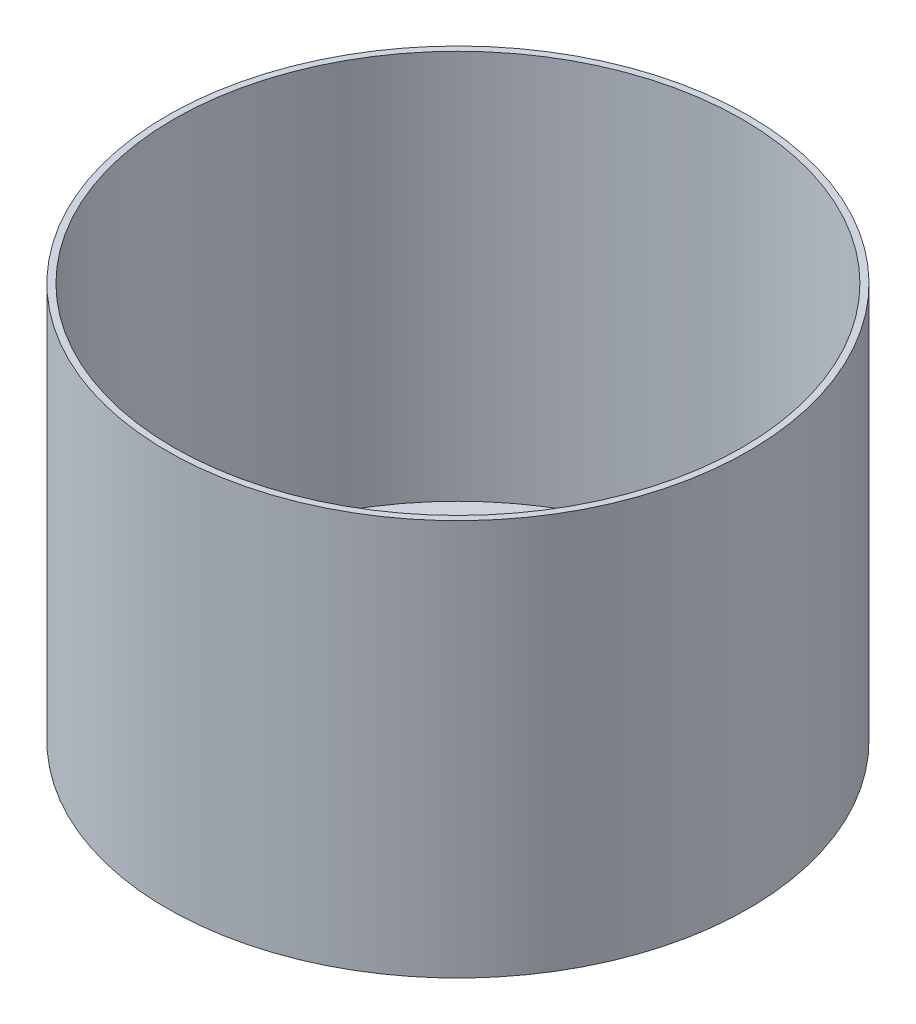
SolidWorks part; units mm, degrees
ref_plane "Front Plane" through (0, 0, 0) normal (0, 0, 1) x (1, 0, 0)
ref_plane "Top Plane" through (0, 0, 0) normal (0, 1, 0) x (1, 0, 0)
ref_plane "Right Plane" through (0, 0, 0) normal (1, 0, 0) x (0, 0, -1)
sketch "Compartment" plane through (0, 0, 0) normal (0, 0, 1) x (1, 0, 0)
  line L3 (115.189, -80) -> (0, -80)
  line L6 (112.649, 76.972) -> (115.189, 76.972)
  line L9 (112.649, 76.972) -> (112.649, -77.46)
  line L10 (112.649, -77.46) -> (0, -77.46)
  line L11 (0, -77.46) -> (0, -80)
  line L14 (115.189, 76.972) -> (115.189, -80)
  dimension "D1" = 154.432
  dimension "D2" = 2.54
  dimension "D5" = 112.649
  dimension "D6" = 2.54
  dimension "D9" = 80
ref_axis "Axis1" through (0, 0, 0) along (0, 1, 0)
revolve "Revolve1" add sketch "Compartment" angle 360 about axis through (0, 0, 0) along (0, 1, 0)
sketch "Motor Hole" plane through (0, -80, 0) normal (0, -1, 0) x (1, 0, 0)
  circle A0 centre (0, 0) radius 25.4
  circle A1 centre (0, 95.25) radius 4.7625
  circle A2 centre (95.25, 0) radius 4.7625
  circle A3 centre (0, -95.25) radius 4.7625
  circle A4 centre (-95.25, 0) radius 4.7625
  circle A5 centre (0, 0) radius 115.189 construction
  point P11 (0, 0)
  point P12 (0, 0)
  dimension "D1" = 50.8
  dimension "D2" = 9.525
  dimension "D3" = 95.25
  dimension "D4" = 0
  dimension "D5" = 95.25
  dimension "D6" = 0
  dimension "D7" = 95.25
  dimension "D8" = 95.25
extrude "Cut-Extrude2" cut sketch "Motor Hole" against normal up to next
sketch "Stablizing poles" plane through (0, -80, 0) normal (0, -1, 0) x (1, 0, 0)
  circle A0 centre (-90, 0) radius 10
  circle A1 centre (90, 0) radius 10
  dimension "D1" = 20
  dimension "D2" = 90
  dimension "D3" = 90
extrude "Boss-Extrude1" [suppressed] add sketch "Stablizing poles" along normal blind 30
